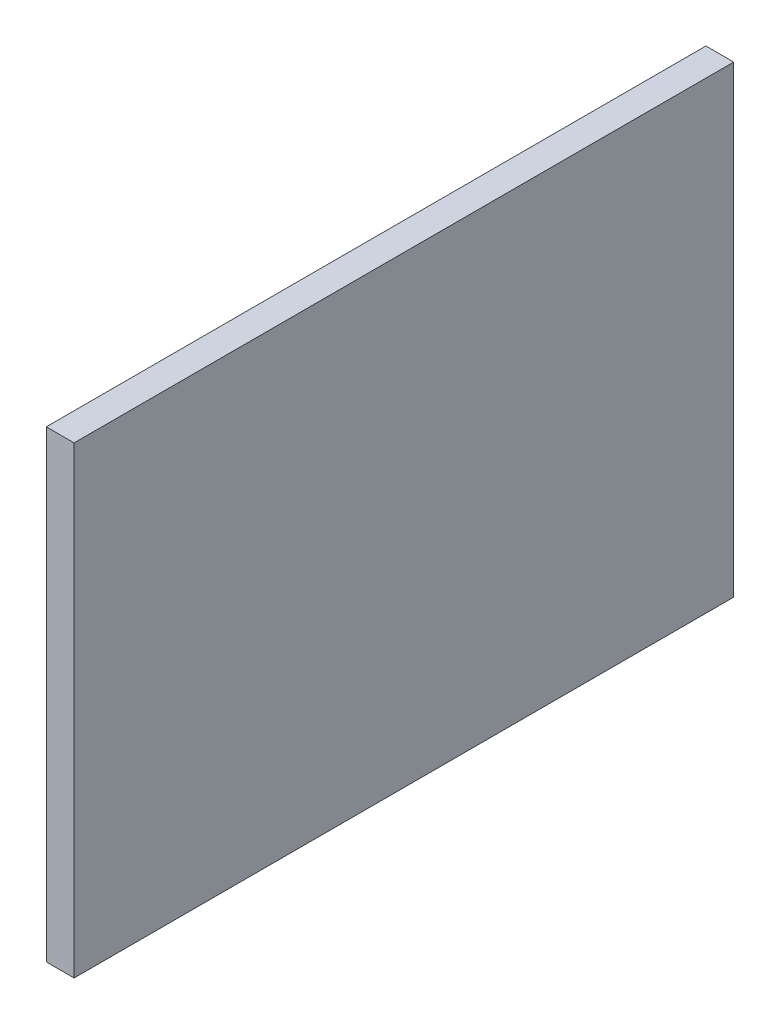
SolidWorks part; units mm, degrees
ref_plane "Front Plane" through (0, 0, 0) normal (0, 0, 1) x (1, 0, 0)
ref_plane "Top Plane" through (0, 0, 0) normal (0, 1, 0) x (1, 0, 0)
ref_plane "Right Plane" through (0, 0, 0) normal (1, 0, 0) x (0, 0, -1)
sketch "Sketch1" plane through (0, 0, 0) normal (1, 0, 0) x (0, 0, -1)
  line L1 (0, 0) -> (427, 0)
  line L2 (0, 0) -> (0, 300)
  line L3 (0, 300) -> (427, 300)
  line L4 (427, 0) -> (427, 300)
  dimension "D1" = 427
  dimension "D2" = 300
extrude "Boss-Extrude1" add sketch "Sketch1" along normal blind 18
